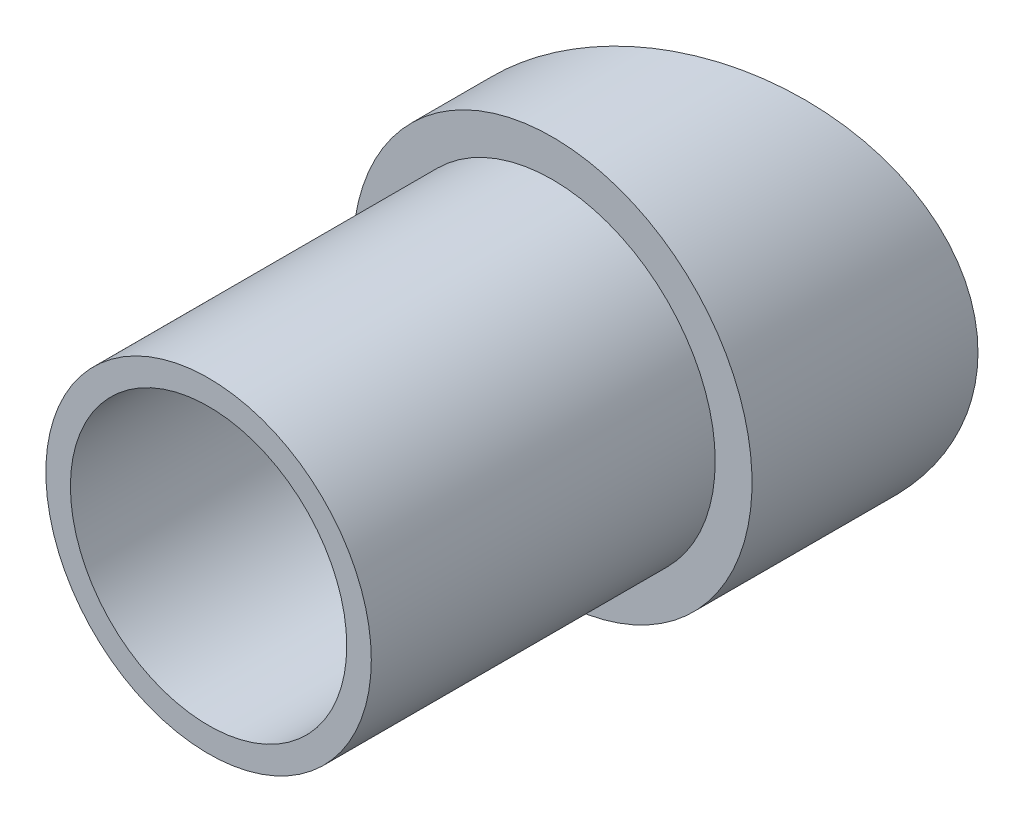
SolidWorks part; units mm, degrees
ref_plane "Front" through (0, 0, 0) normal (0, 0, 1) x (1, 0, 0)
ref_plane "Top" through (0, 0, 0) normal (0, 1, 0) x (1, 0, 0)
ref_plane "Right" through (0, 0, 0) normal (1, 0, 0) x (0, 0, -1)
sketch "Sketch2" plane through (0, 0, 0) normal (0, 0, 1) x (1, 0, 0)
  circle A0 centre (0, 0) radius 13.25
  dimension "D1" = 26.5
extrude "Boss-Extrude1" add sketch "Sketch2" against normal blind 28
sketch "Sketch3" plane through (0, 0, -28) normal (0, 0, -1) x (-1, 0, 0)
  circle A0 centre (0, 0) radius 16.25
  dimension "D1" = 32.5
extrude "Boss-Extrude2" add sketch "Sketch3" along normal blind 28
sketch "Sketch4" plane through (0, 0, 0) normal (0, 1, 0) x (1, 0, 0)
  line L0 (-16.25, 32.6023) -> (16.25, 46.3977)
  line L1 (-16.25, 56) -> (-16.25, 28) construction
  line L2 (16.25, 28) -> (16.25, 56) construction
  line L3 (16.25, 46.3977) -> (16.25, 56)
  line L4 (16.25, 56) -> (-16.25, 56) construction
  line L5 (16.25, 56) -> (-16.25, 56)
  line L6 (-16.25, 56) -> (-16.25, 32.6023)
  line L7 (-13.25, 0) -> (13.25, 0) construction
  line L8 (0, 0) -> (0, 39.5) construction
  dimension "D1" = 23
  dimension "D2" = 39.5
extrude "Cut-Extrude1" cut sketch "Sketch4" against normal through all and the other way through all
sketch "Sketch5" plane through (0, 0, 0) normal (0, 0, 1) x (1, 0, 0)
  circle A0 centre (0, 0) radius 11.25
  dimension "D1" = 22.5
extrude "Cut-Extrude2" cut sketch "Sketch5" against normal offset from surface (38.8435 mm away) 5
sketch "Sketch6" plane through (-14.207, 0, -33.4695) normal (-0.3907, 0, -0.9205) x (-0.9205, 0, 0.3907)
  line L0 (-33.0872, 0) -> (2.2195, 0) construction
  circle A0 centre (-15.4339, 0) radius 2.1
  ellipse E0 centre (-15.4339, 0) end of major axis (2.2195, 0) minor radius 16.25 construction
  dimension "D1" = 4.2
extrude "Cut-Extrude3" cut sketch "Sketch6" against normal up to surface (5 mm away) up to face at (-11.25, 0, -29.2929)
sketch "Sketch7" plane through (-12.2533, 0, -28.867) normal (0.3907, 0, 0.9205) x (0.9205, 0, -0.3907)
  line L1 (19.5339, 0) -> (17.4839, 3.5507)
  line L2 (17.4839, 3.5507) -> (13.3839, 3.5507)
  line L3 (13.3839, 3.5507) -> (11.3339, 0)
  line L4 (11.3339, 0) -> (13.3839, -3.5507)
  line L5 (13.3839, -3.5507) -> (17.4839, -3.5507)
  line L6 (17.4839, -3.5507) -> (19.5339, 0)
  circle A0 centre (15.4339, 0) radius 3.5507 construction
  dimension "D1" = 8.2
extrude "Cut-Extrude4" cut sketch "Sketch7" against normal blind 2
